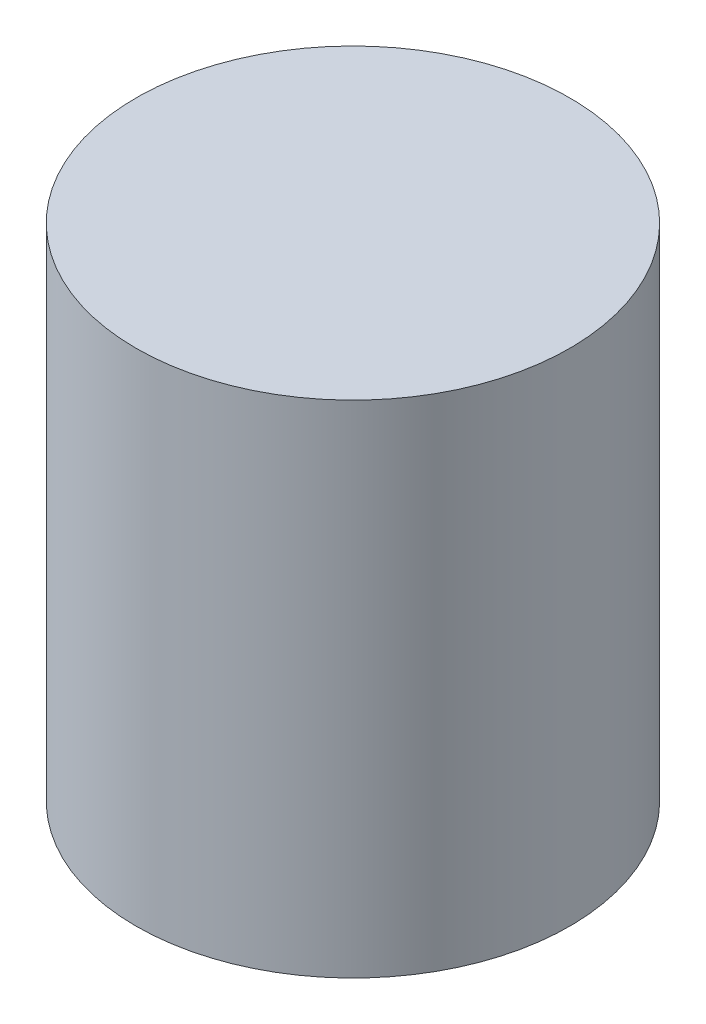
SolidWorks part; units mm, degrees
ref_plane "Front Plane" through (0, 0, 0) normal (0, 0, 1) x (1, 0, 0)
ref_plane "Top Plane" through (0, 0, 0) normal (0, 1, 0) x (1, 0, 0)
ref_plane "Right Plane" through (0, 0, 0) normal (1, 0, 0) x (0, 0, -1)
sketch "Sketch1" plane through (0, 0, 0) normal (0, 0, 1) x (1, 0, 0)
  line L0 (0, 7.5) -> (0, -7.5)
  line L1 (0, -7.5) -> (6.5, -7.5)
  line L3 (0, 7.5) -> (6.5, 7.5)
  line L4 (6.5, -7.5) -> (6.5, 7.5)
  point P0 (0, 0)
  dimension "D2" = 15
revolve "Revolve1" add sketch "Sketch1" angle 360 about L0
sketch "Sketch2" plane through (0, -7.5, 0) normal (0, -1, 0) x (1, 0, 0)
  circle A0 centre (0, 0) radius 4.5
extrude "Cut-Extrude1" cut sketch "Sketch2" against normal blind 13
sketch "Sketch3" plane through (0, 0, 0) normal (0, 0, 1) x (1, 0, 0)
  circle A0 centre (0, 0) radius 2
extrude "Cut-Extrude2" cut sketch "Sketch3" against normal blind 13
